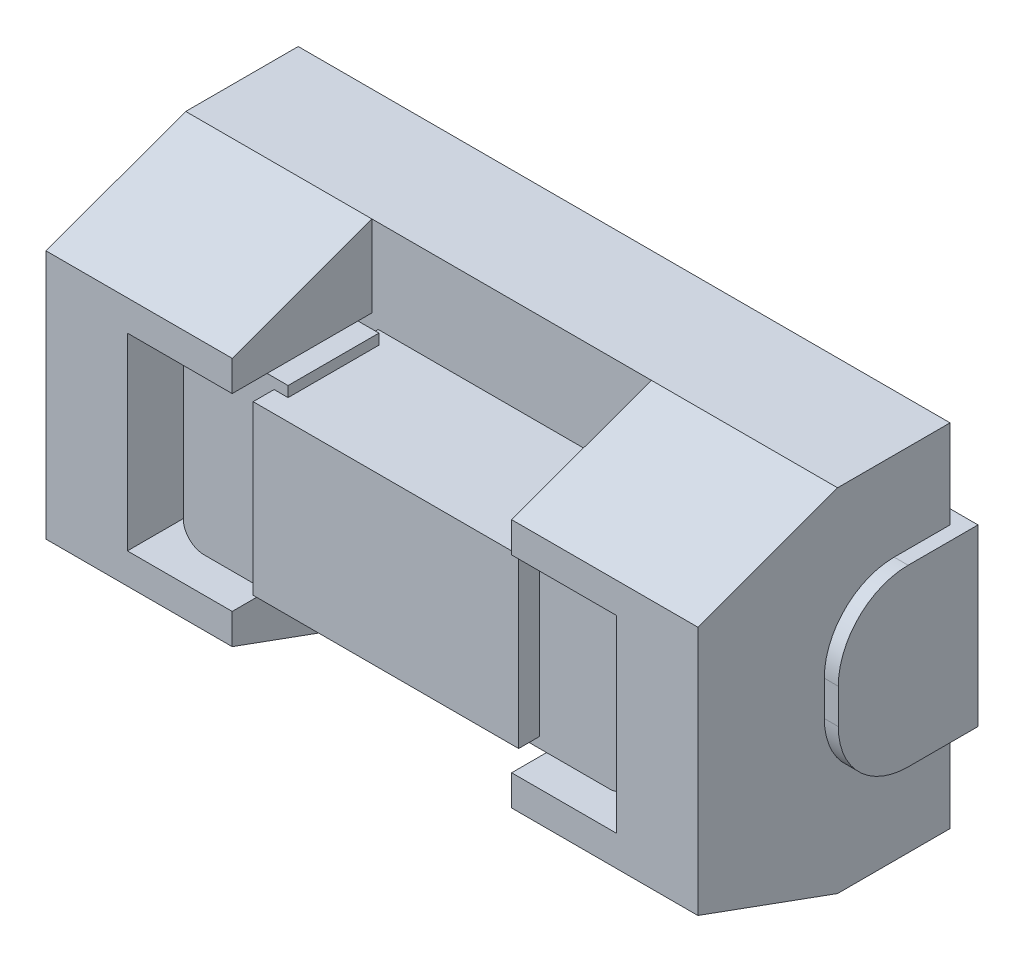
SolidWorks part; units mm, degrees
ref_plane "Plan de face" through (0, 0, 0) normal (0, 0, 1) x (1, 0, 0)
ref_plane "Plan de dessus" through (0, 0, 0) normal (0, 1, 0) x (1, 0, 0)
ref_plane "Plan de droite" through (0, 0, 0) normal (1, 0, 0) x (0, 0, -1)
sketch "Sketch1" plane through (0, 0, 0) normal (0, 0, 1) x (1, 0, 0)
  line L1 (-4.665, 2.515) -> (4.665, 2.515)
  line L2 (-4.665, 2.515) -> (-4.665, -2.515)
  line L3 (-4.665, -2.515) -> (4.665, -2.515)
  line L4 (4.665, 2.515) -> (4.665, -2.515)
  line L5 (-4.665, 2.515) -> (4.665, -2.515) construction
  line L6 (-4.665, -2.515) -> (4.665, 2.515) construction
  point P0 (0, 0)
  dimension "D1" = 5.03
  dimension "D2" = 9.33
extrude "Boss-Extrude1" add sketch "Sketch1" along normal blind 3.61 from offset 0.2
sketch "Sketch2" plane through (0, 0, 3.81) normal (0, 0, 1) x (1, 0, 0)
  line L0 (4.665, 2.515) -> (-4.665, 2.515) construction
  line L1 (-3.5, 1.35) -> (-2, 1.35)
  line L2 (-3.5, 1.35) -> (-3.5, -1.35)
  line L3 (-3.5, -1.35) -> (-2, -1.35)
  line L4 (3.5, 1.35) -> (3.5, -1.35)
  line L5 (-2, 2.515) -> (2, 2.515)
  line L6 (-2, 2.515) -> (-2, 1.35)
  line L7 (-2, -2.515) -> (2, -2.515)
  line L8 (2, 2.515) -> (2, 1.35)
  line L9 (-4.665, -2.515) -> (4.665, -2.515) construction
  line L10 (0, 0.7216) -> (0, 0) construction
  line L11 (0, 0) -> (0.9892, 0) construction
  line L12 (2, 1.35) -> (3.5, 1.35)
  line L13 (-2, -1.35) -> (-2, -2.515)
  line L14 (2, -1.35) -> (3.5, -1.35)
  line L15 (2, -1.35) -> (2, -2.515)
  dimension "D1" = 7
  dimension "D2" = 2.7
  dimension "D3" = 4
extrude "Cut-Extrude1" cut sketch "Sketch2" against normal blind 2
chamfer "Chamfer1" distance 2 angle 20 4 edges at (-3.3325, 2.515, 3.81) (3.3325, 2.515, 3.81) (3.3325, -2.515, 3.81) (-3.3325, -2.515, 3.81)
sketch "Sketch6" plane through (0, 0, 0) normal (0, 1, 0) x (1, 0, 0)
  line L0 (4.665, -2) -> (4.865, -2)
  line L1 (4.665, -1.81) -> (4.665, -0.2) construction
  line L2 (4.865, -2) -> (4.865, 0)
  line L3 (4.865, 0) -> (1, 0)
  line L4 (1, 0) -> (1, -0.2)
  line L5 (-4.665, -0.2) -> (4.665, -0.2) construction
  line L6 (1, -0.2) -> (4.665, -0.2)
  line L7 (4.665, -0.2) -> (4.665, -2)
  dimension "D1" = 0.2
  dimension "D2" = 1
  dimension "D3" = 2
extrude "Boss-Extrude3" add sketch "Sketch6" along normal mid plane 2.5
fillet "Fillet2" radius 1 2 edges at (4.765, -1.25, 2) (4.765, 1.25, 2)
mirror "Mirror1" about plane through (0, 0, 0) normal (1, 0, 0) of "Boss-Extrude3", "Fillet2"
sketch "Sketch7" plane through (0, 0, 1.81) normal (0, 0, 1) x (1, 0, 0)
  line L0 (-2, 1.35) -> (-3.5, 1.35) construction
  line L1 (-3.2, 1.35) -> (-1.7, 1.35)
  line L2 (-3.2, 1.35) -> (-3.2, -1.35)
  line L3 (-3.2, -1.35) -> (-1.7, -1.35)
  line L4 (-1.7, 1.35) -> (-1.7, -1.35)
  line L5 (-3.5, -1.35) -> (-2, -1.35) construction
  dimension "D1" = 1.5
  dimension "D2" = 1.7
extrude "Boss-Extrude4" add sketch "Sketch7" along normal blind 1.3 from offset 0.2 separate body
fillet "Fillet3" radius 0.3 2 edges at (-3.2, -1.35, 2.66) (-3.2, 1.35, 2.66)
mirror "Mirror2" about plane through (0, 0, 0) normal (1, 0, 0) of bodies 108
sketch "Sketch8" plane through (0, 0, 3.31) normal (0, 0, 1) x (1, 0, 0)
  line L0 (0, 0.5772) -> (0, 0) construction
  line L1 (-1.9, 1.2) -> (1.9, 1.2)
  line L2 (-1.9, 1.2) -> (-1.9, -1.2)
  line L3 (-1.9, -1.2) -> (1.9, -1.2)
  line L4 (1.9, 1.2) -> (1.9, -1.2)
  line L5 (0, 0) -> (0.7132, 0) construction
  dimension "D1" = 3.8
  dimension "D2" = 2.4
extrude "Boss-Extrude5" add sketch "Sketch8" against normal offset from surface (1.79 mm away) 0.01 from offset 0.3
